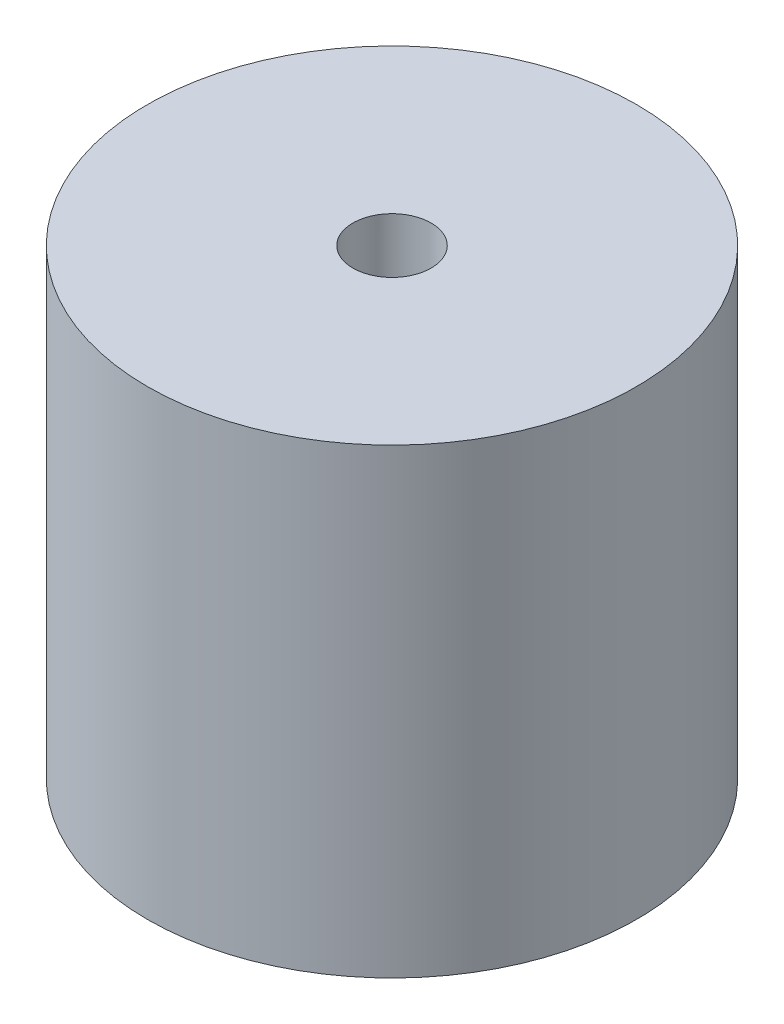
SolidWorks part; units mm, degrees
ref_plane "Front Plane" through (0, 0, 0) normal (0, 0, 1) x (1, 0, 0)
ref_plane "Top Plane" through (0, 0, 0) normal (0, 1, 0) x (1, 0, 0)
ref_plane "Right Plane" through (0, 0, 0) normal (1, 0, 0) x (0, 0, -1)
sketch "Sketch2" plane through (0, 0, 0) normal (0, 1, 0) x (1, 0, 0)
  circle A0 centre (0, 0) radius 15.875
  dimension "D1" = 31.75
extrude "Boss-Extrude1" add sketch "Sketch2" along normal blind 29.972
sketch "Sketch3" plane through (0, 0, 0) normal (0, -1, 0) x (1, 0, 0)
  circle A0 centre (0, 0) radius 12.065
  dimension "D1" = 24.13
extrude "Cut-Extrude1" cut sketch "Sketch3" against normal blind 24.13
sketch "Sketch4" plane through (0, 29.972, 0) normal (0, 1, 0) x (1, 0, 0)
  circle A0 centre (0, 0) radius 2.54
  dimension "D1" = 5.08
extrude "Cut-Extrude2" cut sketch "Sketch4" against normal up to next
